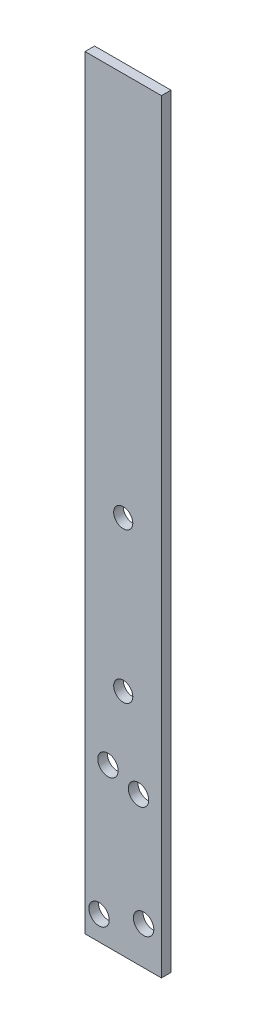
SolidWorks part; units mm, degrees
ref_plane "Front Plane" through (0, 0, 0) normal (0, 0, 1) x (1, 0, 0)
ref_plane "Top Plane" through (0, 0, 0) normal (0, 1, 0) x (1, 0, 0)
ref_plane "Right Plane" through (0, 0, 0) normal (1, 0, 0) x (0, 0, -1)
sketch "Sketch2" plane through (0, 0, 0) normal (0, 0, 1) x (1, 0, 0)
  line L13 (0, 0) -> (0, 381)
  line L16 (11.43, 78.6905) -> (26.67, 78.6905) construction
  line L17 (6.985, 12.0155) -> (29.21, 12.0155) construction
  line L18 (0, 0) -> (38.1, 0)
  line L19 (38.1, 0) -> (38.1, 381)
  line L20 (38.1, 381) -> (0, 381)
  circle A6 centre (11.43, 78.6905) radius 5.08
  circle A7 centre (26.67, 73.6105) radius 5.08
  circle A8 centre (6.985, 12.0155) radius 5.08
  circle A9 centre (29.21, 19.0005) radius 5.08
  circle A10 centre (19.05, 114.3) radius 4.7625
  circle A11 centre (19.05, 189.23) radius 4.7625
  point P0 (16.3897, 165.1)
  point P9 (19.05, 381)
  dimension "D6" = 74.93
  dimension "D19" = 10.16
  dimension "D4" = 9.525
  dimension "D3" = 38.1
  dimension "D5" = 114.3
  dimension "D7" = 381
  dimension "D8" = 12.0155
  dimension "D9" = 19.0005
  dimension "D10" = 78.6905
  dimension "D11" = 73.6105
  dimension "D12" = 6.985
  dimension "D13" = 11.43
  dimension "D24" = 15.24
  dimension "D25" = 22.225
extrude "Boss-Extrude2" add sketch "Sketch2" along normal blind 4.7625
